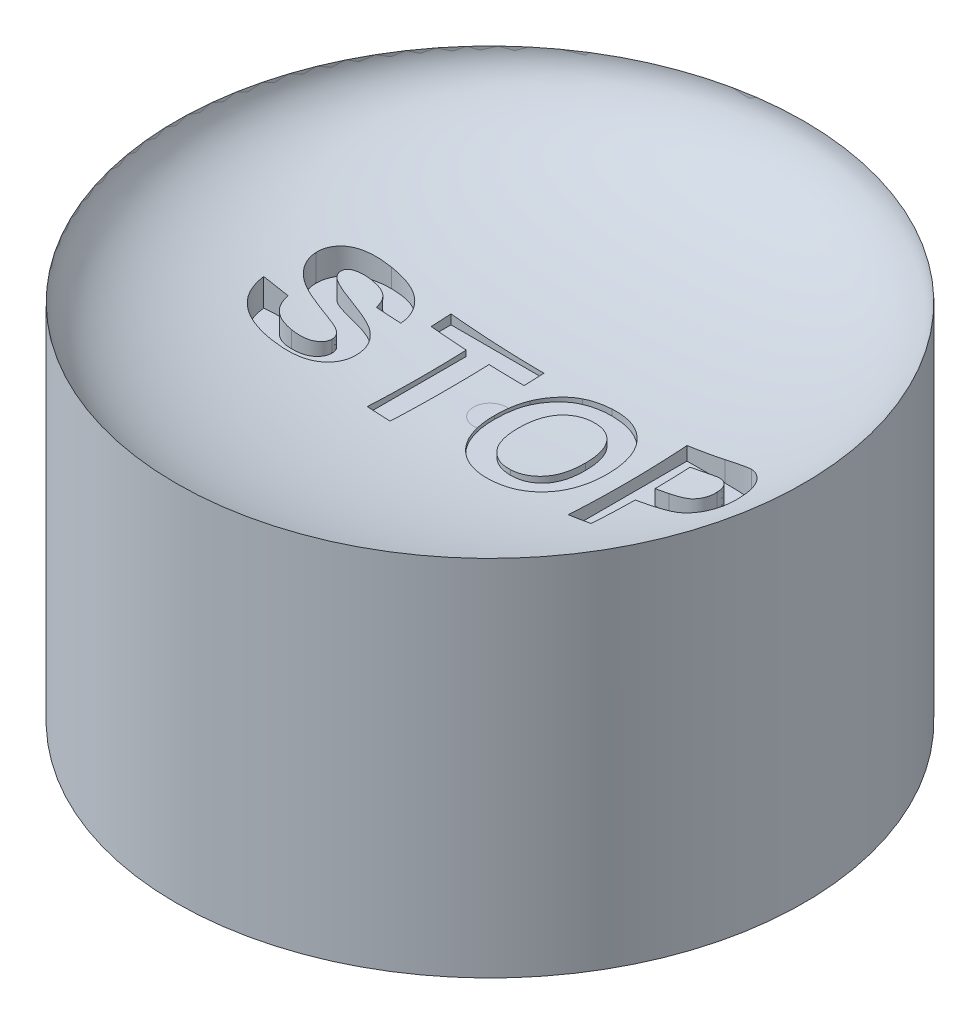
SolidWorks part; units mm, degrees
material "ABS"
ref_plane "Front Plane" through (0, 0, 0) normal (0, 0, 1) x (1, 0, 0)
ref_plane "Top Plane" through (0, 0, 0) normal (0, 1, 0) x (1, 0, 0)
ref_plane "Right Plane" through (0, 0, 0) normal (1, 0, 0) x (0, 0, -1)
sketch "Sketch1" plane through (0, 0, 0) normal (0, 1, 0) x (1, 0, 0)
  circle A0 centre (0, 0) radius 9.5
  dimension "D1" = 19
extrude "Boss-Extrude1" add sketch "Sketch1" along normal blind 8
sketch "Sketch6" plane through (0, 0, 0) normal (1, 0, 0) x (0, 0, -1)
  line L0 (0, 8) -> (0, 11.4053) construction
  line L1 (9.5, 8) -> (-9.5, 8) construction
  line L2 (-9.5, 8) -> (-9.5, 11)
  line L3 (-9.5, 8) -> (-0.5, 8)
  ellipse E0 centre (-0.5, 11) end of major axis (8.5, 11) minor radius 3 (-9.5, 11) -> (-0.5, 8) ccw
  dimension "D1" = 3
  dimension "D2" = 9
revolve "Revolve4" add sketch "Sketch6" angle 360 about L0
ref_plane "Plane1" through (0, 10, 0) normal (0, 1, 0) x (1, 0, 0)
sketch "Sketch7" plane through (0, 10, 0) normal (0, 1, 0) x (1, 0, 0)
  text T0 "STOP" font "Arial" height in points 14
extrude "Cut-Extrude1" cut sketch "Sketch7" against normal blind 2.1
